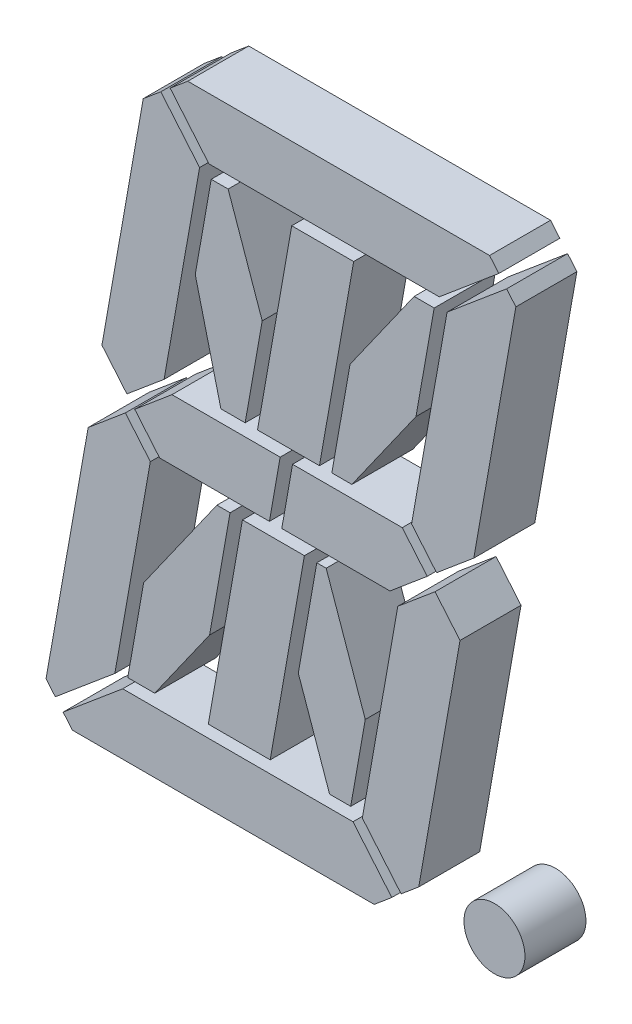
SolidWorks part; units mm, degrees
ref_plane "Спереди" through (0, 0, 0) normal (0, 0, 1) x (1, 0, 0)
ref_plane "Сверху" through (0, 0, 0) normal (0, 1, 0) x (1, 0, 0)
ref_plane "Справа" through (0, 0, 0) normal (1, 0, 0) x (0, 0, -1)
sketch "Эскиз5" plane through (0, 0, 0) normal (0, 0, 1) x (1, 0, 0)
  line L0 (-2.9354, 0.6286) -> (-2.2586, 4.4672)
  line L1 (-2.2586, 4.4672) -> (-1.97, 4.7093)
  line L2 (-1.97, 4.7093) -> (-1.3341, 3.9514)
  line L3 (-1.3341, 3.9514) -> (-1.9157, 0.6532)
  line L4 (-1.9157, 0.6532) -> (-2.5262, 0.1409)
  line L7 (-2.5262, 0.1409) -> (-2.9354, 0.6286)
  line L8 (-3.1615, -0.6532) -> (-2.5509, -0.1409)
  line L11 (-2.5509, -0.1409) -> (-2.1417, -0.6286)
  line L12 (-2.1417, -0.6286) -> (-2.7233, -3.9268)
  line L13 (-2.7233, -3.9268) -> (-3.6999, -4.7463)
  line L14 (-3.6999, -4.7463) -> (-3.8513, -4.5658)
  line L15 (-3.8513, -4.5658) -> (-3.1615, -0.6532)
  line L16 (-3.5713, -4.8995) -> (-2.5947, -4.08)
  line L17 (-2.5947, -4.08) -> (1.1809, -4.08)
  line L18 (1.1809, -4.08) -> (1.8168, -4.8379)
  line L19 (1.8168, -4.8379) -> (1.5282, -5.08)
  line L20 (1.5282, -5.08) -> (-3.4199, -5.08)
  line L21 (-3.4199, -5.08) -> (-3.5713, -4.8995)
  line L22 (1.9157, -0.6532) -> (2.5262, -0.1409)
  line L25 (2.5262, -0.1409) -> (2.9354, -0.6286)
  line L26 (2.9354, -0.6286) -> (2.2586, -4.4672)
  line L27 (2.2586, -4.4672) -> (1.97, -4.7093)
  line L28 (1.97, -4.7093) -> (1.3341, -3.9514)
  line L29 (1.3341, -3.9514) -> (1.9157, -0.6532)
  line L30 (2.1417, 0.6286) -> (2.5509, 0.1409)
  line L33 (2.5509, 0.1409) -> (3.1615, 0.6532)
  line L34 (3.1615, 0.6532) -> (3.8513, 4.5658)
  line L35 (3.8513, 4.5658) -> (3.6999, 4.7463)
  line L36 (3.6999, 4.7463) -> (2.7233, 3.9268)
  line L37 (2.7233, 3.9268) -> (2.1417, 0.6286)
  line L38 (-1.8168, 4.8379) -> (-1.5282, 5.08)
  line L39 (-1.5282, 5.08) -> (3.4199, 5.08)
  line L40 (3.4199, 5.08) -> (3.5713, 4.8995)
  line L41 (3.5713, 4.8995) -> (2.5947, 4.08)
  line L42 (2.5947, 4.08) -> (-1.1809, 4.08)
  line L43 (-1.1809, 4.08) -> (-1.8168, 4.8379)
  line L44 (-1.9885, -0.5) -> (-0.1897, -0.5)
  line L45 (-0.1897, -0.5) -> (-0.0134, 0.5)
  line L46 (-0.0134, 0.5) -> (-1.7871, 0.5)
  line L47 (-1.7871, 0.5) -> (-2.3977, -0.0123)
  line L48 (-2.3977, -0.0123) -> (-1.9885, -0.5)
  line L49 (0.1897, 0.5) -> (1.9885, 0.5)
  line L50 (1.9885, 0.5) -> (2.3977, 0.0123)
  line L51 (2.3977, 0.0123) -> (1.7871, -0.5)
  line L52 (1.7871, -0.5) -> (0.0134, -0.5)
  line L53 (0.0134, -0.5) -> (0.1897, 0.5)
  point P2 (0, 0)
  point P12 (0, 0)
sketch "Эскиз6" plane through (0, 0, 0) normal (0, 0, 1) x (1, 0, 0)
  line L0 (-0.3843, 0.7) -> (0.6311, 0.7)
  line L1 (-0.3843, 0.7) -> (0.1764, 3.88)
  line L2 (0.6311, 0.7) -> (1.1919, 3.88)
  line L3 (0.1764, 3.88) -> (1.1919, 3.88)
  line L4 (-0.6311, -0.7) -> (-1.1919, -3.88)
  line L5 (-0.6311, -0.7) -> (0.3843, -0.7)
  line L6 (-1.1919, -3.88) -> (-0.1764, -3.88)
  line L7 (0.3843, -0.7) -> (-0.1764, -3.88)
sketch "Эскиз7" plane through (0, 0, 0) normal (0, 0, 1) x (1, 0, 0)
  line L0 (-2.2513, -2.4022) -> (-2.5119, -3.88)
  line L2 (-2.5119, -3.88) -> (-2.0704, -3.88)
  line L4 (-2.0704, -3.88) -> (-1.17, -2.6044)
  line L6 (-1.17, -2.6044) -> (-0.8342, -0.7)
  line L8 (-0.8342, -0.7) -> (-1.0498, -0.7)
  line L9 (-1.0498, -0.7) -> (-2.2513, -2.4022)
  line L12 (0.5874, -0.7) -> (0.7408, -0.7)
  line L14 (0.7408, -0.7) -> (1.3821, -2.5274)
  line L16 (1.3821, -2.5274) -> (1.1436, -3.88)
  line L17 (1.1436, -3.88) -> (0.797, -3.88)
  line L18 (0.797, -3.88) -> (0.2843, -2.419)
  line L21 (0.2843, -2.419) -> (0.5874, -0.7)
  line L22 (2.1831, 3.88) -> (2.5119, 3.88)
  line L24 (2.5119, 3.88) -> (2.2138, 2.1894)
  line L26 (2.2138, 2.1894) -> (1.1625, 0.7)
  line L28 (1.1625, 0.7) -> (0.8342, 0.7)
  line L29 (0.8342, 0.7) -> (1.1325, 2.3916)
  line L30 (1.1325, 2.3916) -> (2.1831, 3.88)
  line L31 (-0.9849, 0.7) -> (-0.5874, 0.7)
  line L32 (-0.5874, 0.7) -> (-0.3075, 2.2872)
  line L33 (-0.3075, 2.2872) -> (-0.8664, 3.88)
  line L34 (-0.8664, 3.88) -> (-1.1436, 3.88)
  line L35 (-1.1436, 3.88) -> (-1.4053, 2.3957)
  line L37 (-1.4053, 2.3957) -> (-0.9849, 0.7)
sketch "Эскиз8" plane through (0, 0, 0) normal (0, 0, 1) x (1, 0, 0)
  circle A0 centre (3.5, -4.58) radius 0.5
extrude "Бобышка-Вытянуть1" add sketch "Эскиз5" along normal blind 1
extrude "Бобышка-Вытянуть2" add sketch "Эскиз6" along normal blind 1 separate body
extrude "Бобышка-Вытянуть3" add sketch "Эскиз8" along normal blind 1 separate body
extrude "Бобышка-Вытянуть4" add sketch "Эскиз7" along normal blind 1 separate body
